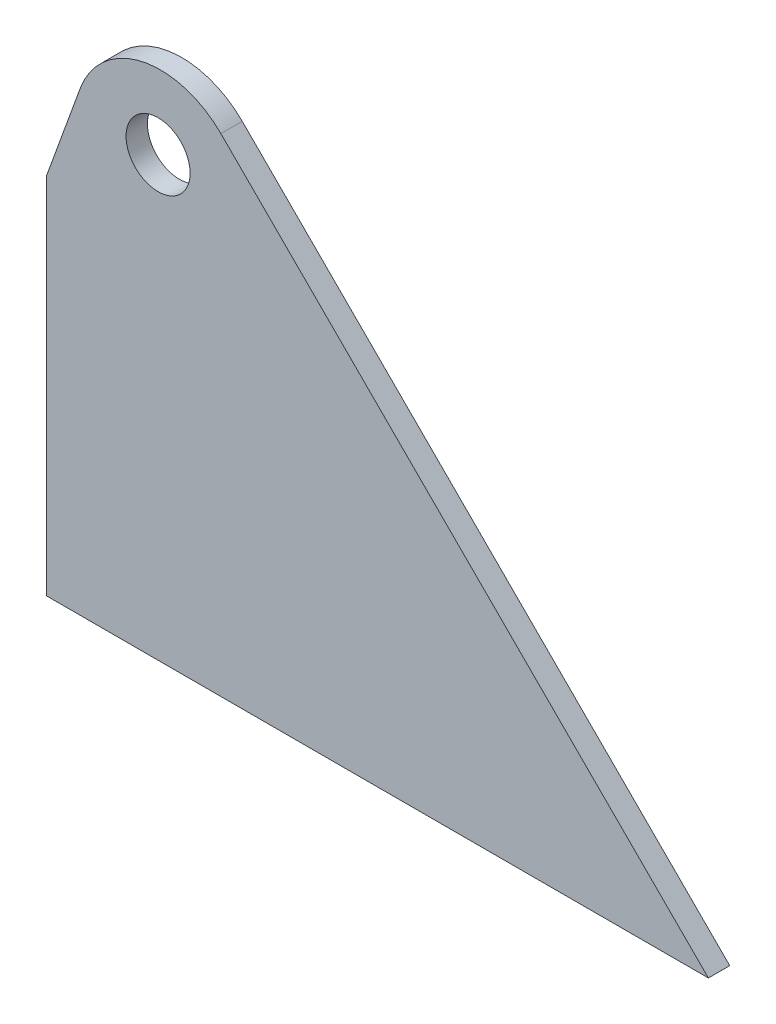
SolidWorks part; units mm, degrees
ref_plane "Plan de face" through (0, 0, 0) normal (0, 0, 1) x (1, 0, 0)
ref_plane "Plan de dessus" through (0, 0, 0) normal (0, 1, 0) x (1, 0, 0)
ref_plane "Plan de droite" through (0, 0, 0) normal (1, 0, 0) x (0, 0, -1)
sketch "Esquisse1" plane through (0, 0, 0) normal (0, 0, 1) x (1, 0, 0)
  line L0 (0, 0) -> (0, 170)
  line L1 (0, 170) -> (18.1985, 220) construction
  line L2 (18.1985, 220) -> (90, 220) construction
  line L3 (18.1985, 220) -> (15.8839, 213.6407) construction
  line L4 (310, 0) -> (0, 0)
  line L5 (0, 170) -> (140, 170) construction
  line L6 (310, 0) -> (140, 170)
  line L7 (140, 170) -> (90, 220)
  line L8 (90, 220) -> (81.7559, 228.2441)
  line L9 (90, 220) -> (90, 0) construction
  line L10 (53.4716, 199.9599) -> (44.814, 239.0117) construction
  line L11 (53.4716, 199.9599) -> (52.3542, 205) construction
  line L12 (15.8839, 213.6407) -> (0, 170)
  arc A0 (81.7559, 228.2441) -> (15.8839, 213.6407) centre (53.4716, 199.9599) ccw
  circle A1 centre (52.3542, 205) radius 15
  dimension "D4" = 40
  dimension "D5" = 30
  dimension "D6" = 15
  dimension "D1" = 170
  dimension "D2" = 70
  dimension "D3" = 45
  dimension "D7" = 90
  dimension "D8" = 50
extrude "Boss.-Extru.1" add sketch "Esquisse1" along normal blind 10
